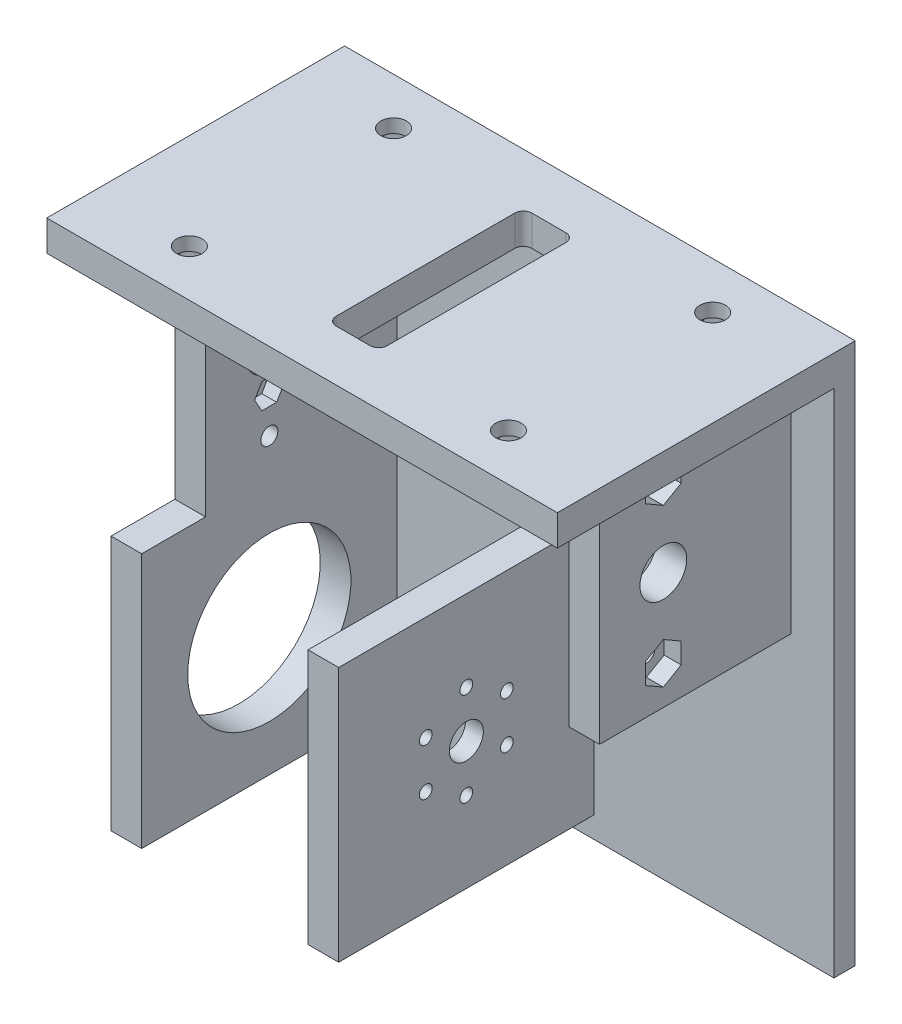
SolidWorks part; units mm, degrees
ref_plane "Front Plane" through (0, 0, 0) normal (0, 0, 1) x (1, 0, 0)
ref_plane "Top Plane" through (0, 0, 0) normal (0, 1, 0) x (1, 0, 0)
ref_plane "Right Plane" through (0, 0, 0) normal (1, 0, 0) x (0, 0, -1)
sketch "Sketch1" plane through (0, 0, 0) normal (0, 1, 0) x (1, 0, 0)
  line L0 (0, 18.2197) -> (0, -18.3609) construction
  line L1 (-19.3496, 0) -> (20.197, 0) construction
  line L2 (-37.5, 0) -> (-37.5, -10) construction
  line L3 (60, 35) -> (-60, 35)
  line L4 (-60, 35) -> (-60, -35)
  line L5 (60, -35) -> (-60, -35)
  line L6 (60, 35) -> (60, -35)
  line L7 (6, 23) -> (-6, 23)
  line L8 (-6, 23) -> (-6, -23)
  line L9 (6, -23) -> (-6, -23)
  line L10 (6, 23) -> (6, -23)
  circle A0 centre (-37.5, 0) radius 10 construction
  circle A6 centre (-37.5, 24) radius 3
  circle A7 centre (-37.5, 24) radius 3.4 construction
  circle A8 centre (-37.5, -24) radius 3
  circle A9 centre (-37.5, -24) radius 3.4 construction
  circle A10 centre (37.5, 24) radius 3
  circle A11 centre (37.5, 24) radius 3.4 construction
  circle A12 centre (37.5, 0) radius 10 construction
  circle A13 centre (37.5, -24) radius 3.4 construction
  circle A14 centre (37.5, -24) radius 3
  point P18 (-60, 0)
  point P20 (0, 35)
  point P21 (0, -35)
  point P33 (-6, 0)
  point P35 (0, -23)
  point P36 (0, 23)
  dimension "D1" = 20
  dimension "D3" = 6.8
  dimension "D4" = 48
  dimension "D5" = 75
  dimension "D2" = 6
  dimension "D6" = 120
  dimension "D7" = 70
  dimension "D8" = 12
  dimension "D9" = 46
extrude "Boss-Extrude1" add sketch "Sketch1" along normal blind 7.2
fillet "Fillet1" radius 2 4 edges at (6, 3.6, 23) (-6, 3.6, 23) (6, 3.6, -23) (-6, 3.6, -23)
sketch "Sketch2" plane through (0, 0, 0) normal (0, -1, 0) x (1, 0, 0)
  line L0 (-60, -35) -> (-60, -30)
  line L1 (-60, -35) -> (-60, 35) construction
  line L2 (-60, -30) -> (60, -30)
  line L3 (60, 35) -> (60, -35) construction
  line L4 (60, -30) -> (60, -35)
  line L5 (60, -35) -> (-60, -35)
  dimension "D1" = 5
extrude "Boss-Extrude2" add sketch "Sketch2" along normal blind 120
sketch "Sketch9" plane through (0, 0, -30) normal (0, 0, 1) x (1, 0, 0)
  line L0 (0, 0) -> (0, -123.6159) construction
  line L2 (60, 0) -> (-60, 0) construction
  line L3 (-49.9, 0) -> (-42.7, 0)
  line L4 (-49.9, 0) -> (-49.9, -55)
  line L5 (-49.9, -55) -> (-42.7, -55)
  line L6 (-42.7, 0) -> (-42.7, -55)
  line L7 (49.9, -55) -> (42.7, -55)
  line L8 (42.7, 0) -> (42.7, -55)
  line L9 (49.9, 0) -> (42.7, 0)
  line L10 (49.9, 0) -> (49.9, -55)
  dimension "D1" = 7.2
  dimension "D2" = 55
  dimension "D3" = 85.4
extrude "Boss-Extrude3" add sketch "Sketch9" along normal blind 45
sketch "Sketch10" plane through (-49.9, 0, 0) normal (-1, 0, 0) x (0, 0, 1)
  line L0 (0, 0) -> (0, -55) construction
  line L1 (15, -55) -> (-30, -55) construction
  line L2 (-30, -27.5) -> (15, -27.5) construction
  line L3 (-30, 0) -> (-30, -55) construction
  line L4 (15, 0) -> (15, -55) construction
  circle A0 centre (0, -27.5) radius 5.5
  circle A1 centre (0, -27.5) radius 18.5 construction
  circle A2 centre (0, -9) radius 2
  circle A3 centre (0, -46) radius 2
  dimension "D1" = 11
  dimension "D2" = 37
  dimension "D3" = 4
extrude "Cut-Extrude5" cut sketch "Sketch10" against normal through all both and the other way through all
sketch "Sketch8" plane through (0, 0, 0) normal (0, -1, 0) x (1, 0, 0)
  line L1 (42.7, 27.0022) -> (37.5, 30.0044)
  line L2 (37.5, 30.0044) -> (32.3, 27.0022)
  line L3 (32.3, 27.0022) -> (32.3, 20.9978)
  line L4 (32.3, 20.9978) -> (37.5, 17.9956)
  line L5 (37.5, 17.9956) -> (42.7, 20.9978)
  line L6 (42.7, 20.9978) -> (42.7, 27.0022)
  line L7 (-32.3, 27.0022) -> (-37.5, 30.0044)
  line L8 (-37.5, 30.0044) -> (-42.7, 27.0022)
  line L9 (-42.7, 27.0022) -> (-42.7, 20.9978)
  line L10 (-42.7, 20.9978) -> (-37.5, 17.9956)
  line L11 (-37.5, 17.9956) -> (-32.3, 20.9978)
  line L12 (-32.3, 20.9978) -> (-32.3, 27.0022)
  line L13 (42.7, -20.9978) -> (37.5, -17.9956)
  line L14 (37.5, -17.9956) -> (32.3, -20.9978)
  line L15 (32.3, -20.9978) -> (32.3, -27.0022)
  line L16 (32.3, -27.0022) -> (37.5, -30.0044)
  line L17 (37.5, -30.0044) -> (42.7, -27.0022)
  line L18 (42.7, -27.0022) -> (42.7, -20.9978)
  line L19 (-32.3, -20.9978) -> (-37.5, -17.9956)
  line L20 (-37.5, -17.9956) -> (-42.7, -20.9978)
  line L21 (-42.7, -20.9978) -> (-42.7, -27.0022)
  line L22 (-42.7, -27.0022) -> (-37.5, -30.0044)
  line L23 (-37.5, -30.0044) -> (-32.3, -27.0022)
  line L24 (-32.3, -27.0022) -> (-32.3, -20.9978)
  circle A0 centre (37.5, 24) radius 5.2 construction
  circle A1 centre (-37.5, 24) radius 5.2 construction
  circle A2 centre (37.5, -24) radius 5.2 construction
  circle A3 centre (-37.5, -24) radius 5.2 construction
  dimension "D1" = 10.4
  dimension "D2" = 10.4
  dimension "D3" = 10.4
  dimension "D4" = 10.4
extrude "Cut-Extrude4" cut sketch "Sketch8" against normal blind 4
sketch "Sketch11" plane through (-49.9, 0, 0) normal (-1, 0, 0) x (0, 0, 1)
  line L1 (0, -13.8497) -> (4.2, -11.4249)
  line L2 (4.2, -11.4249) -> (4.2, -6.5751)
  line L3 (4.2, -6.5751) -> (0, -4.1503)
  line L4 (0, -4.1503) -> (-4.2, -6.5751)
  line L5 (-4.2, -6.5751) -> (-4.2, -11.4249)
  line L6 (-4.2, -11.4249) -> (0, -13.8497)
  line L7 (0, -50.8497) -> (4.2, -48.4249)
  line L8 (4.2, -48.4249) -> (4.2, -43.5751)
  line L9 (4.2, -43.5751) -> (0, -41.1503)
  line L10 (0, -41.1503) -> (-4.2, -43.5751)
  line L11 (-4.2, -43.5751) -> (-4.2, -48.4249)
  line L12 (-4.2, -48.4249) -> (0, -50.8497)
  circle A0 centre (0, -9) radius 4.2 construction
  circle A1 centre (0, -46) radius 4.2 construction
  dimension "D1" = 8.4
  dimension "D2" = 8.4
extrude "Cut-Extrude6" cut sketch "Sketch11" against normal blind 4
sketch "Sketch12" plane through (49.9, 0, 0) normal (1, 0, 0) x (0, 0, -1)
  line L1 (0, -13.8497) -> (4.2, -11.4249)
  line L2 (4.2, -11.4249) -> (4.2, -6.5751)
  line L3 (4.2, -6.5751) -> (0, -4.1503)
  line L4 (0, -4.1503) -> (-4.2, -6.5751)
  line L5 (-4.2, -6.5751) -> (-4.2, -11.4249)
  line L6 (-4.2, -11.4249) -> (0, -13.8497)
  line L7 (0, -41.1503) -> (-4.2, -43.5751)
  line L8 (-4.2, -43.5751) -> (-4.2, -48.4249)
  line L9 (-4.2, -48.4249) -> (0, -50.8497)
  line L10 (0, -50.8497) -> (4.2, -48.4249)
  line L11 (4.2, -48.4249) -> (4.2, -43.5751)
  line L12 (4.2, -43.5751) -> (0, -41.1503)
  circle A0 centre (0, -9) radius 4.2 construction
  circle A1 centre (0, -46) radius 4.2 construction
  dimension "D1" = 8.4
  dimension "D2" = 8.4
extrude "Cut-Extrude7" cut sketch "Sketch12" against normal blind 4
sketch "Sketch15" plane through (-49.9, 0, 0) normal (-1, 0, 0) x (0, 0, 1)
  circle A0 centre (0, -27.5) radius 9.525 construction
  circle A1 centre (0, -17.975) radius 1.5
  circle A2 centre (0, -37.025) radius 1.5
  dimension "D1" = 19.05
  dimension "D2" = 3
extrude "Cut-Extrude8" cut sketch "Sketch15" against normal up to surface (7.2 mm away) up to face at (-42.7, -48, 0)
sketch "Sketch16" plane through (-42.7, 0, 0) normal (1, 0, 0) x (0, 0, -1)
  line L1 (1.7321, -14.975) -> (-1.7321, -14.975)
  line L2 (-1.7321, -14.975) -> (-3.4641, -17.975)
  line L3 (-3.4641, -17.975) -> (-1.7321, -20.975)
  line L4 (-1.7321, -20.975) -> (1.7321, -20.975)
  line L5 (1.7321, -20.975) -> (3.4641, -17.975)
  line L6 (3.4641, -17.975) -> (1.7321, -14.975)
  line L7 (1.7321, -34.025) -> (-1.7321, -34.025)
  line L8 (-1.7321, -34.025) -> (-3.4641, -37.025)
  line L9 (-3.4641, -37.025) -> (-1.7321, -40.025)
  line L10 (-1.7321, -40.025) -> (1.7321, -40.025)
  line L11 (1.7321, -40.025) -> (3.4641, -37.025)
  line L12 (3.4641, -37.025) -> (1.7321, -34.025)
  circle A0 centre (0, -17.975) radius 3 construction
  circle A1 centre (0, -37.025) radius 3 construction
  dimension "D1" = 6
  dimension "D2" = 6
extrude "Cut-Extrude9" cut sketch "Sketch16" against normal blind 3.5
sketch "Sketch17" plane through (0, 0, -30) normal (0, 0, 1) x (1, 0, 0)
  line L0 (0, 0) -> (0, -120) construction
  line L2 (60, -120) -> (-60, -120) construction
  line L3 (3.6, -55) -> (-3.6, -55)
  line L4 (-3.6, -55) -> (-3.6, -115)
  line L5 (-3.6, -115) -> (3.6, -115)
  line L6 (3.6, -55) -> (3.6, -115)
  line L7 (-49.9, -55) -> (-42.7, -55) construction
  line L9 (-42.7, -55) -> (-49.9, -55)
  line L10 (-49.9, -55) -> (-49.9, -115)
  line L11 (-49.9, -115) -> (-42.7, -115)
  line L12 (-42.7, -115) -> (-42.7, -55)
  point P11 (0, -55)
  point P14 (0, -115)
  point P16 (0, -120)
  point P21 (0, 0)
  point P23 (0, 0)
  dimension "D1" = 60
  dimension "D2" = 7.2
  dimension "D3" = 0
extrude "Boss-Extrude4" add sketch "Sketch17" along normal blind 60
sketch "Sketch18" plane through (3.6, 0, 0) normal (1, 0, 0) x (0, 0, -1)
  line L0 (0, 0) -> (0, -85) construction
  line L1 (-30, -85) -> (30, -85) construction
  line L2 (-30, -115) -> (-30, -55) construction
  line L3 (30, -115) -> (30, -55) construction
  circle A0 centre (0, -85) radius 4
  dimension "D1" = 8
extrude "Cut-Extrude10" cut sketch "Sketch18" against normal through all both and the other way through all
sketch "Sketch19" plane through (3.6, 0, 0) normal (1, 0, 0) x (0, 0, -1)
  circle A0 centre (0, -85) radius 11 construction
  circle A1 centre (0, -74) radius 1.5
  circle A2 centre (9.5263, -79.5) radius 1.5
  circle A3 centre (9.5263, -90.5) radius 1.5
  circle A4 centre (0, -96) radius 1.5
  circle A5 centre (-9.5263, -90.5) radius 1.5
  circle A6 centre (-9.5263, -79.5) radius 1.5
  point P5 (0, -85)
  point P17 (0, -85)
  dimension "D1" = 22
  dimension "D2" = 3
  dimension "D3" = 6
extrude "Cut-Extrude11" cut sketch "Sketch19" against normal up to surface (7.2 mm away) up to face at (-3.6, -81, 0)
sketch "Sketch20" plane through (-3.6, 0, 0) normal (-1, 0, 0) x (0, 0, 1)
  circle A0 centre (0, -85) radius 8.5
  dimension "D1" = 17
extrude "Cut-Extrude12" cut sketch "Sketch20" against normal blind 3
sketch "Sketch21" plane through (-49.9, 0, 0) normal (-1, 0, 0) x (0, 0, 1)
  circle A0 centre (0, -85) radius 19.175
  dimension "D1" = 38.35
extrude "Cut-Extrude13" cut sketch "Sketch21" against normal up to surface (7.2 mm away) up to face at (-42.7, -89, 0)
